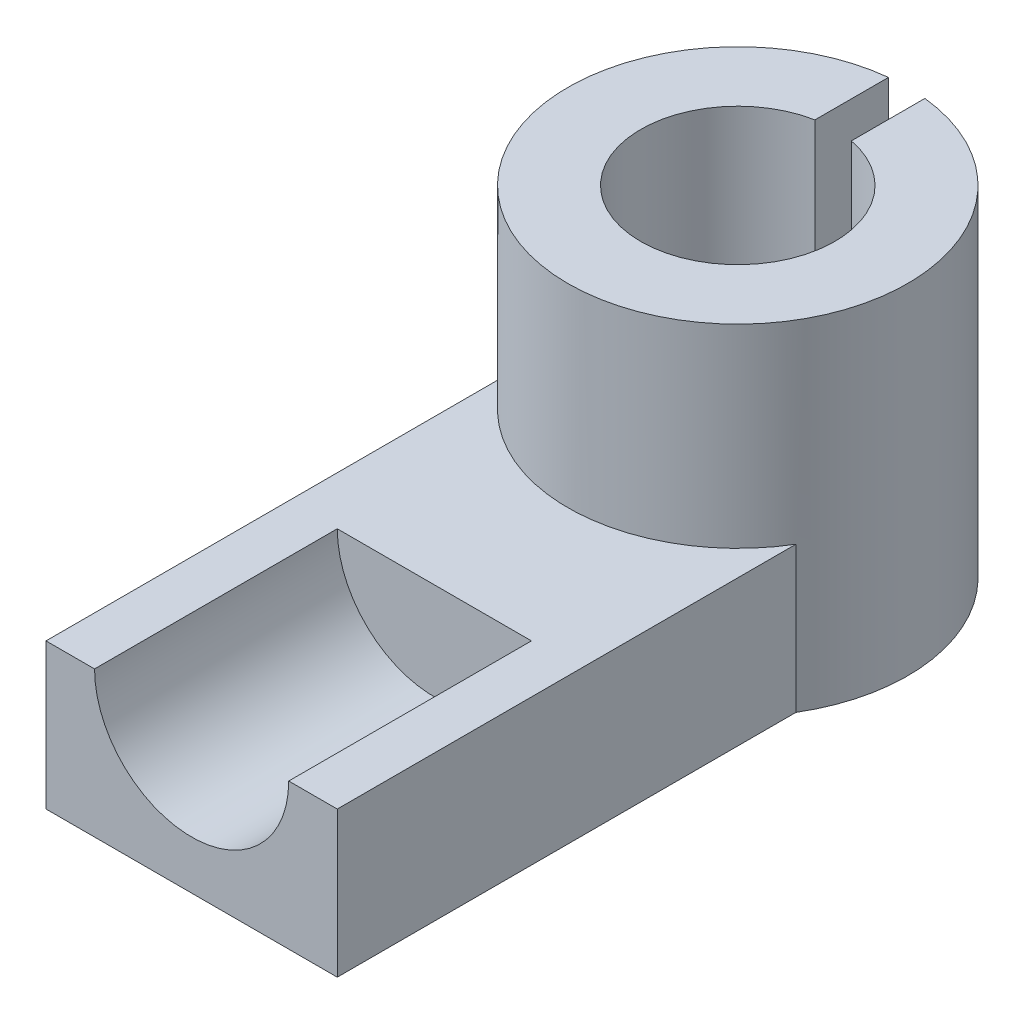
SolidWorks part; units mm, degrees
ref_plane "Ön Düzlem" through (0, 0, 0) normal (0, 0, 1) x (1, 0, 0)
ref_plane "Üst Düzlem" through (0, 0, 0) normal (0, 1, 0) x (1, 0, 0)
ref_plane "Sağ Düzlem" through (0, 0, 0) normal (1, 0, 0) x (0, 0, -1)
sketch "Sketch1" plane through (0, 0, 0) normal (0, 1, 0) x (1, 0, 0)
  circle A0 centre (0, 0) radius 28
  circle A1 centre (0, 0) radius 16
  dimension "D1" = 32
  dimension "D2" = 56
extrude "Boss-Extrude1" add sketch "Sketch1" along normal blind 56
sketch "Sketch2" plane through (0, 56, 0) normal (0, 1, 0) x (1, 0, 0)
  circle A0 centre (0, 0) radius 16 construction
  point P0 (0, 16)
sketch "Sketch3" plane through (0, 56, 0) normal (0, 1, 0) x (1, 0, 0)
  line L1 (-3, 34.7133) -> (3, 34.7133)
  line L2 (-3, 34.7133) -> (-3, -2.7133)
  line L3 (-3, -2.7133) -> (3, -2.7133)
  line L4 (3, 34.7133) -> (3, -2.7133)
  line L5 (-3, 34.7133) -> (3, -2.7133) construction
  line L6 (-3, -2.7133) -> (3, 34.7133) construction
  point P0 (0, 16)
  dimension "D1" = 6
extrude "Cut-Extrude1" cut sketch "Sketch3" against normal up to next
sketch "Sketch4" plane through (0, 0, 0) normal (0, -1, 0) x (1, 0, 0)
  line L0 (0, 0) -> (0, 68.6397) construction
  line L1 (-24, 90) -> (24, 90)
  line L2 (-24, 90) -> (-24, 14.4222)
  line L4 (24, 90) -> (24, 14.4222)
  arc A0 (3, -27.8388) -> (-3, -27.8388) centre (0, 0) ccw construction
  arc A1 (24, 14.4222) -> (-24, 14.4222) centre (0, 0) ccw
  dimension "D1" = 90
  dimension "D2" = 48
extrude "Boss-Extrude3" add sketch "Sketch4" against normal blind 24 contours L2 A1 L4 L1
sketch "Sketch5" plane through (0, 0, 90) normal (0, 0, 1) x (1, 0, 0)
  line L0 (-24, 24) -> (24, 24) construction
  circle A0 centre (0, 24) radius 16
  dimension "D1" = 32
extrude "Cut-Extrude2" cut sketch "Sketch5" against normal blind 40
